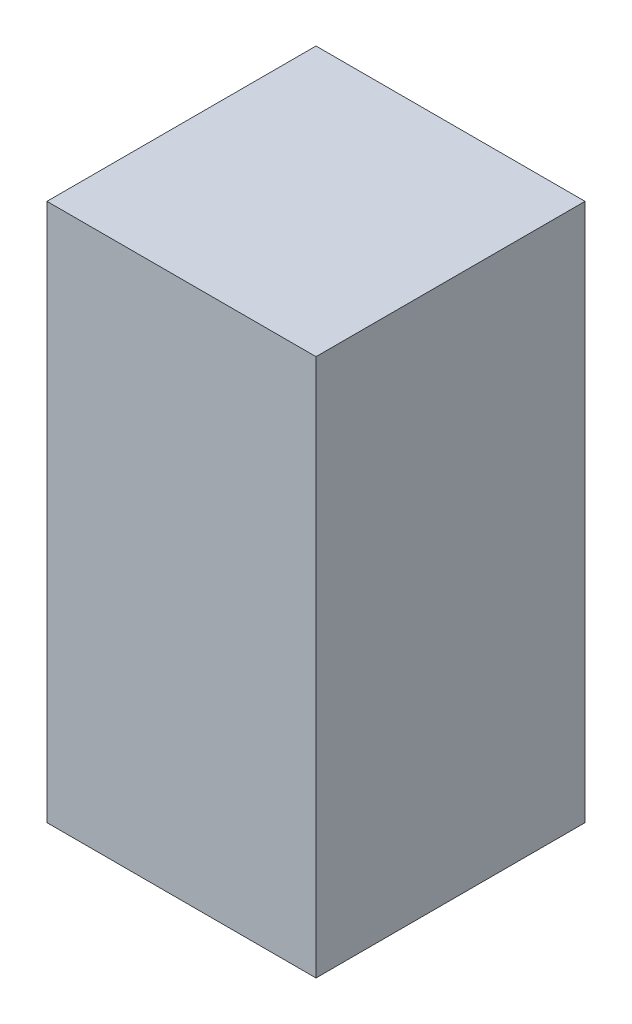
SolidWorks part; units mm, degrees
ref_plane "Front Plane" through (0, 0, 0) normal (0, 0, 1) x (1, 0, 0)
ref_plane "Top Plane" through (0, 0, 0) normal (0, 1, 0) x (1, 0, 0)
ref_plane "Right Plane" through (0, 0, 0) normal (1, 0, 0) x (0, 0, -1)
sketch "Sketch1" plane through (0, 0, 0) normal (0, 1, 0) x (1, 0, 0)
  line L1 (-12.7, -12.7) -> (12.7, -12.7)
  line L2 (-12.7, -12.7) -> (-12.7, 12.7)
  line L3 (-12.7, 12.7) -> (12.7, 12.7)
  line L4 (12.7, -12.7) -> (12.7, 12.7)
  line L5 (-12.7, -12.7) -> (12.7, 12.7) construction
  line L6 (-12.7, 12.7) -> (12.7, -12.7) construction
  point P0 (0, 0)
  dimension "D1" = 25.4
  dimension "D2" = 25.4
extrude "Boss-Extrude1" add sketch "Sketch1" along normal blind 50.8
